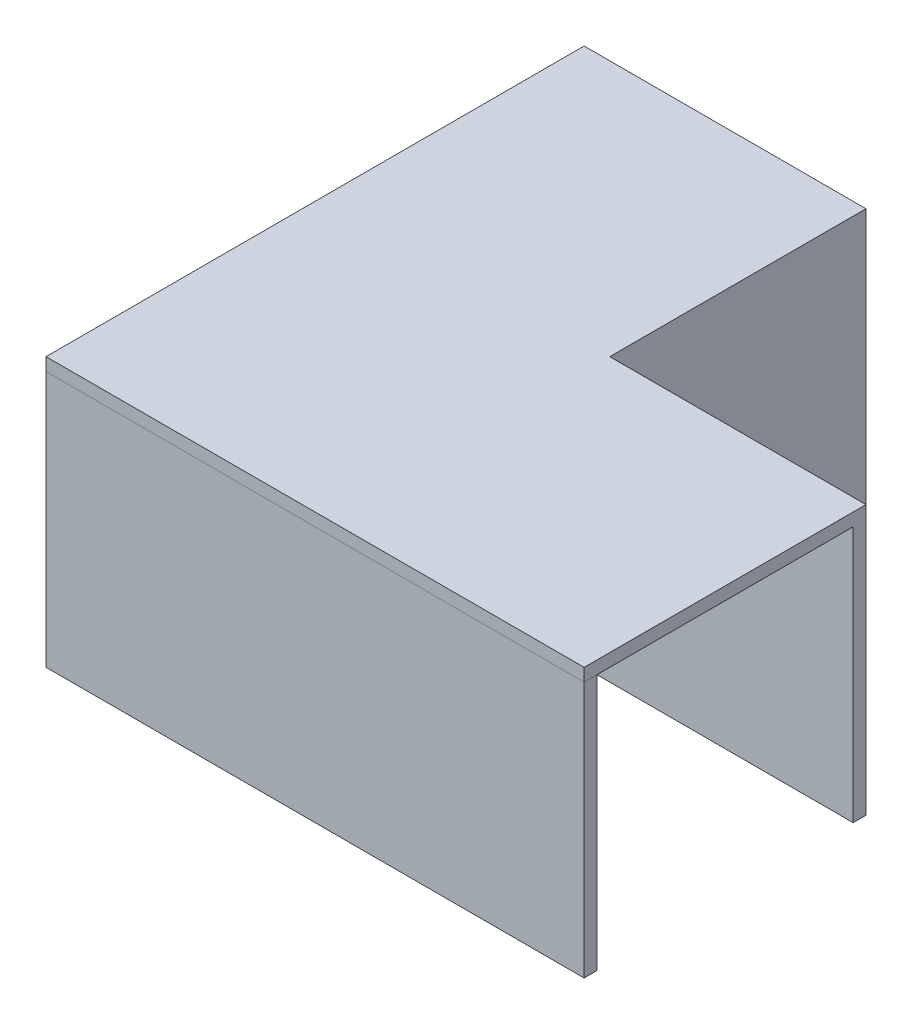
SolidWorks part; units mm, degrees
ref_plane "Front Plane" through (0, 0, 0) normal (0, 0, 1) x (1, 0, 0)
ref_plane "Top Plane" through (0, 0, 0) normal (0, 1, 0) x (1, 0, 0)
ref_plane "Right Plane" through (0, 0, 0) normal (1, 0, 0) x (0, 0, -1)
sketch "Sketch1" plane through (0, 0, 0) normal (0, 1, 0) x (1, 0, 0)
  line L0 (0, 0) -> (508, 0)
  line L1 (508, 0) -> (508, 254)
  line L2 (508, 254) -> (254, 254)
  line L3 (254, 254) -> (254, 508)
  line L4 (254, 508) -> (0, 508)
  line L5 (0, 508) -> (0, 0)
  line L6 (-12.7, -12.7) -> (520.7, -12.7)
  line L7 (520.7, -12.7) -> (520.7, 266.7)
  line L8 (520.7, 266.7) -> (266.7, 266.7)
  line L9 (266.7, 266.7) -> (266.7, 520.7)
  line L10 (266.7, 520.7) -> (-12.7, 520.7)
  line L11 (-12.7, 520.7) -> (-12.7, -12.7)
  dimension "D1" = 254
  dimension "D2" = 254
  dimension "D3" = 254
  dimension "D4" = 254
  dimension "D5" = 12.7
extrude "Boss-Extrude1" add sketch "Sketch1" along normal blind 254
sketch "Sketch2" plane through (508, 0, 0) normal (-1, 0, 0) x (0, 0, 1)
  line L1 (-254, 254) -> (0, 254)
  line L2 (-254, 254) -> (-254, 0)
  line L3 (-254, 0) -> (0, 0)
  line L4 (0, 254) -> (0, 0)
extrude "Cut-Extrude1" cut sketch "Sketch2" against normal blind 254
sketch "Sketch3" plane through (0, 0, -508) normal (0, 0, 1) x (1, 0, 0)
  line L1 (0, 254) -> (254, 254)
  line L2 (0, 254) -> (0, 0)
  line L3 (0, 0) -> (254, 0)
  line L4 (254, 254) -> (254, 0)
extrude "Cut-Extrude2" cut sketch "Sketch3" against normal blind 254
sketch "Sketch4" plane through (0, 254, 0) normal (0, 1, 0) x (1, 0, 0)
  line L0 (-12.7, -12.7) -> (520.7, -12.7) construction
  line L1 (-12.7, 520.7) -> (266.7, 520.7)
  line L2 (-12.7, 520.7) -> (-12.7, -12.7)
  line L3 (-12.7, -12.7) -> (266.7, -12.7)
  line L4 (266.7, 520.7) -> (266.7, -12.7)
  line L6 (266.7, 266.7) -> (266.7, 520.7) construction
  line L8 (520.7, 266.7) -> (266.7, 266.7)
  line L9 (520.7, 266.7) -> (520.7, -12.7)
  line L10 (520.7, -12.7) -> (266.7, -12.7)
  line L11 (266.7, 266.7) -> (266.7, -12.7)
  line M2 (0, 0) -> (0, 520.7)
  line M3 (0, 520.7) -> (-12.7, 520.7)
  line M4 (-12.7, 520.7) -> (-12.7, -12.7)
  line M5 (-12.7, -12.7) -> (520.7, -12.7)
  line M6 (520.7, -12.7) -> (520.7, 0)
  line M7 (520.7, 0) -> (0, 0)
extrude "Boss-Extrude2" add sketch "Sketch4" along normal blind 12.7 contours L4 L1 M2 M7 | L9 L8 L4 M7 | L4 M7 M2 M3 M4 M5 | L4 M7 M5 M6
